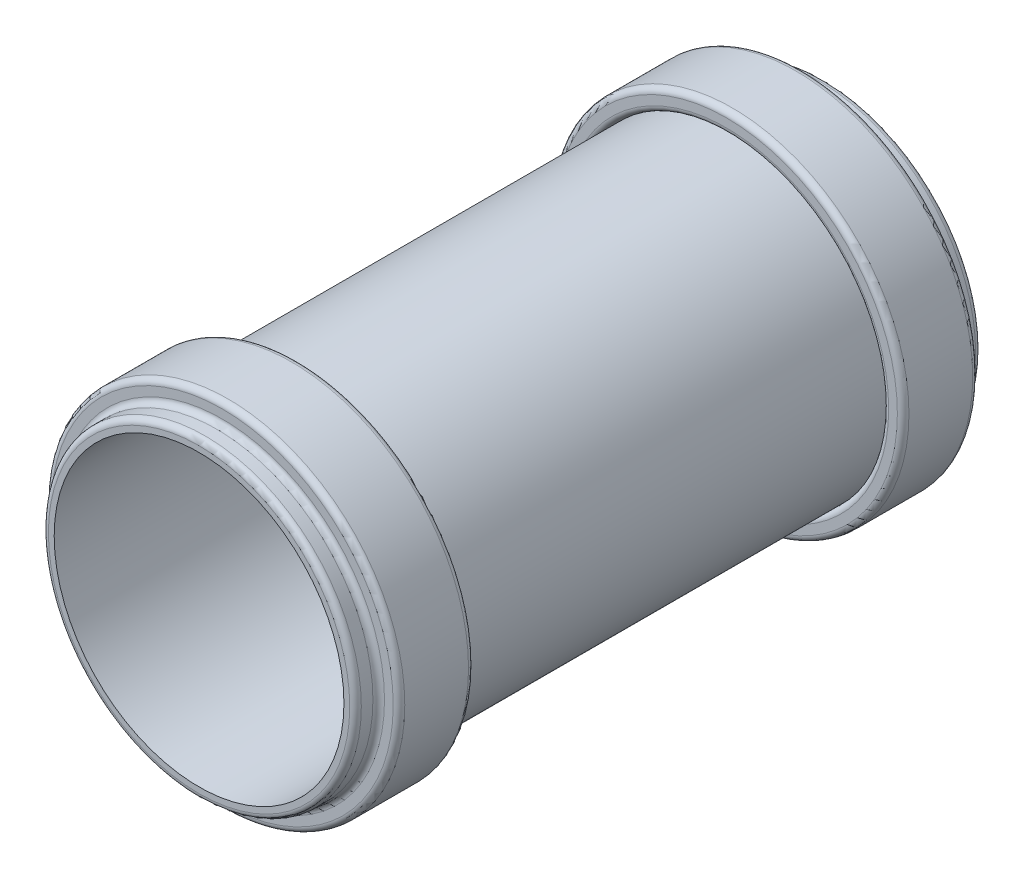
SolidWorks part; units mm, degrees
ref_plane "Спереди" through (0, 0, 0) normal (0, 0, 1) x (1, 0, 0)
ref_plane "Сверху" through (0, 0, 0) normal (0, 1, 0) x (1, 0, 0)
ref_plane "Справа" through (0, 0, 0) normal (1, 0, 0) x (0, 0, -1)
sketch "Эскиз1" plane through (0, 0, 0) normal (0, 0, 1) x (1, 0, 0)
  circle A0 centre (0, 0) radius 27
  circle A1 centre (0, 0) radius 25
  dimension "D1" = 54
  dimension "D2" = 50
extrude "Бобышка-Вытянуть1" add sketch "Эскиз1" along normal blind 74
sketch "Эскиз2" plane through (0, 0, 0) normal (0, 0, -1) x (-1, 0, 0)
  circle A0 centre (0, 0) radius 30.5
  circle A2 centre (0, 0) radius 27
  dimension "D1" = 61
extrude "Бобышка-Вытянуть2" add sketch "Эскиз2" along normal blind 13 separate body
sketch "Эскиз3" plane through (0, 0, 74) normal (0, 0, 1) x (1, 0, 0)
  circle A0 centre (0, 0) radius 30.5
  circle A1 centre (0, 0) radius 27
  dimension "D1" = 61
extrude "Бобышка-Вытянуть3" add sketch "Эскиз3" along normal blind 13 separate body
sketch "Эскиз4" plane through (0, 0, 74) normal (0, 0, 1) x (1, 0, 0)
  circle A0 centre (0, 0) radius 27
  circle A1 centre (0, 0) radius 25
extrude "Бобышка-Вытянуть4" add sketch "Эскиз4" along normal blind 17 and the other way blind 91
fillet "Скругление1" radius 1 4 edges at (-30.5, 0, -13) (-27, 0, -13) (-30.5, 0, 0) (-27, 0, 0)
fillet "Скругление2" radius 1 4 edges at (30.5, 0, 87) (27, 0, 87) (27, 0, 74) (30.5, 0, 74)
fillet "Скругление3" radius 1 2 edges at (27, 0, 91) (27, 0, -17)
